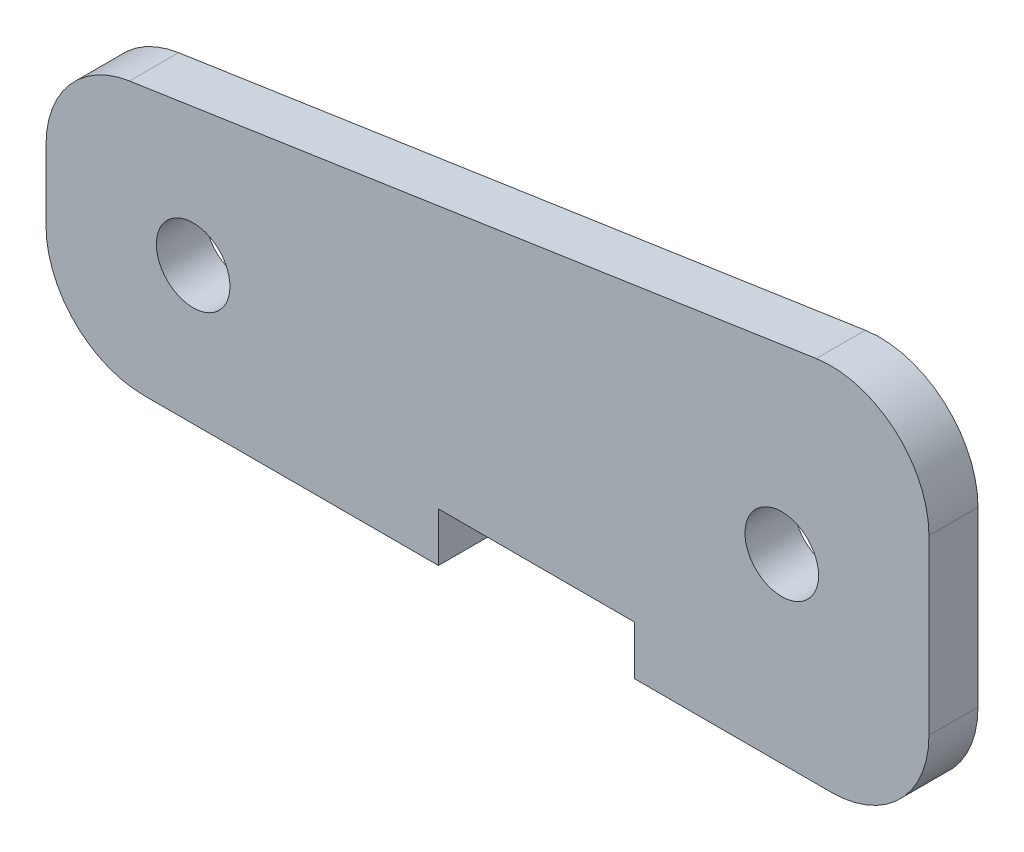
SolidWorks part; units mm, degrees
ref_plane "Front Plane" through (0, 0, 0) normal (0, 0, 1) x (1, 0, 0)
ref_plane "Top Plane" through (0, 0, 0) normal (0, 1, 0) x (1, 0, 0)
ref_plane "Right Plane" through (0, 0, 0) normal (1, 0, 0) x (0, 0, -1)
sketch "Sketch1" plane through (0, 0, 0) normal (0, 0, 1) x (1, 0, 0)
  line L0 (-288.925, 0) -> (-307.975, 0)
  line L10 (-266.7, 0) -> (-266.7, 23.495)
  line L11 (-304.8, 0) -> (-304.8, 17.78)
  line L13 (-314.325, 10.8827) -> (-314.325, 6.35)
  line L14 (-257.175, 17.5502) -> (-257.175, 6.35)
  line L15 (-308.917, 17.1625) -> (-264.467, 23.83)
  line L17 (-288.925, 0) -> (-288.925, 3.175)
  line L18 (-288.925, 3.175) -> (-276.225, 3.175)
  line L19 (-276.225, 0) -> (-276.225, 3.175)
  line L21 (-263.525, 0) -> (-276.225, 0)
  circle A0 centre (-304.8, 8.89) radius 2.3813
  circle A1 centre (-266.7, 11.7475) radius 2.3813
  arc A2 (-257.175, 17.5502) -> (-264.467, 23.83) centre (-263.525, 17.5502) ccw
  arc A3 (-257.175, 6.35) -> (-263.525, 0) centre (-263.525, 6.35) cw
  arc A4 (-314.325, 6.35) -> (-307.975, 0) centre (-307.975, 6.35) ccw
  arc A5 (-314.325, 10.8827) -> (-308.917, 17.1625) centre (-307.975, 10.8827) cw
  dimension "D9" = 4.7625
  dimension "D10" = 4.7625
  dimension "D2" = 6.35
  dimension "D7" = 9.525
  dimension "D8" = 9.525
  dimension "D11" = 12.7
  dimension "D12" = 9.525
  dimension "D13" = 3.175
extrude "Boss-Extrude1" add sketch "Sketch1" along normal blind 3.175 contours A5 L13 A4 L0 L11 A0 L15 | A1 L10 L15 L11 A0 L0 L17 L18 L19 L21 | A3 L14 A2 L15 L10 A1 L21
